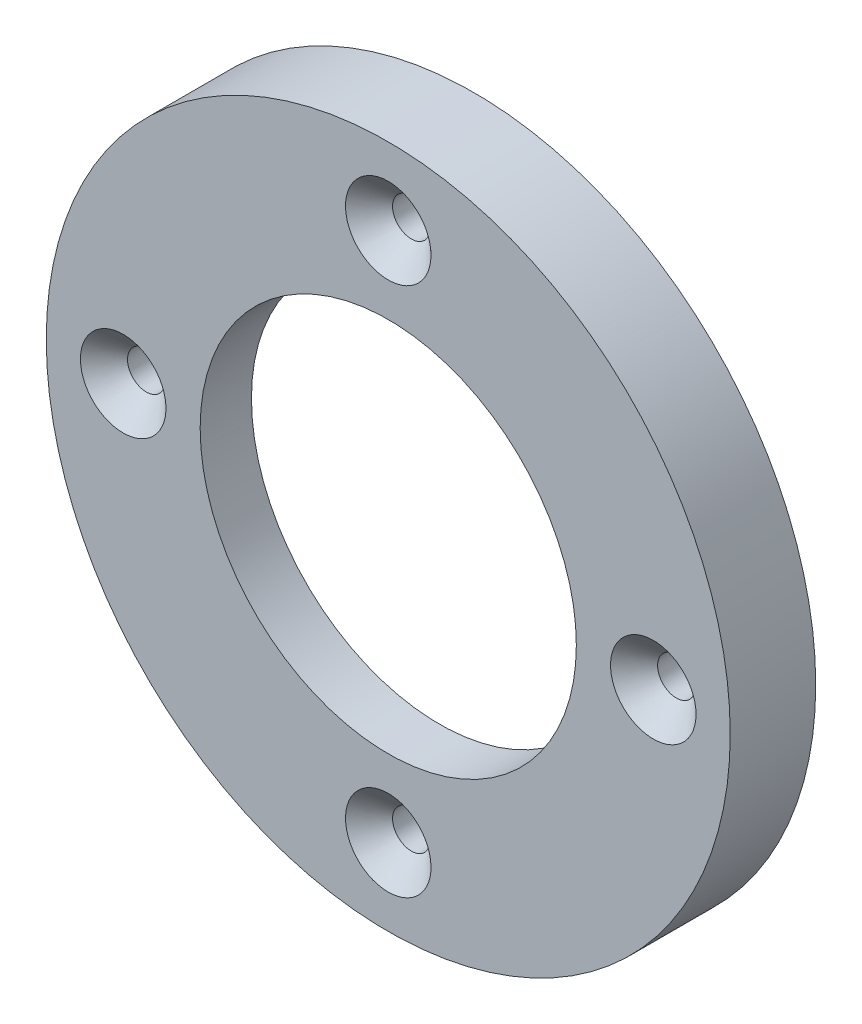
SolidWorks part; units mm, degrees
material "ABS"
ref_plane "Спереди" through (0, 0, 0) normal (0, 0, 1) x (1, 0, 0)
ref_plane "Сверху" through (0, 0, 0) normal (0, 1, 0) x (1, 0, 0)
ref_plane "Справа" through (0, 0, 0) normal (1, 0, 0) x (0, 0, -1)
sketch "Эскиз1" plane through (0, 0, 0) normal (0, 0, 1) x (1, 0, 0)
  arc A0 (-17.6855, -3.3502) -> (-3.3502, -17.6855) centre (0, 0) ccw
  circle A1 centre (0, 0) radius 15.5 construction
  arc A6 (-3.3502, 17.6855) -> (-17.6855, -3.3502) centre (0, 0) ccw
  arc A7 (17.6855, -3.3502) -> (-3.3502, 17.6855) centre (0, 0) ccw
  arc A8 (-3.3502, -17.6855) -> (17.6855, -3.3502) centre (0, 0) ccw
  point P18 (0, 0)
  dimension "D1" = 36
  dimension "D2" = 31
extrude "Бобышка-Вытянуть1" add sketch "Эскиз1" along normal blind 3
sketch "Эскиз2" plane through (0, 0, 3) normal (0, 0, 1) x (1, 0, 0)
  circle A0 centre (0, 0) radius 11
  dimension "D1" = 22
extrude "Вырез-Вытянуть1" cut sketch "Эскиз2" against normal through all
sketch "Эскиз3" plane through (0, 0, 3) normal (0, 0, 1) x (1, 0, 0)
  circle A0 centre (-15.5, 0) radius 2.2
  point P12 (0, 0)
  dimension "D1" = 4.4
  dimension "D2" = 15.5
sketch "Эскиз5" plane through (0, 0, 3) normal (0, 0, 1) x (1, 0, 0)
  circle A0 centre (0, 0) radius 18
  circle A1 centre (0, 0) radius 20
  dimension "D1" = 36
  dimension "D2" = 40
extrude "Бобышка-Вытянуть2" add sketch "Эскиз5" against normal blind 5
ref_axis "Ось1" through (-15.5, 0, -24.0809) along (0, 0, 1)
sketch "Эскиз6" plane through (0, 0, 0) normal (0, 1, 0) x (1, 0, 0)
  line L0 (-16.6, -1.648) -> (-18, -3)
  line L1 (-18, -3) -> (-15.5, -3)
  line L2 (-15.5, -1.648) -> (-15.5, -3)
  line L3 (-16.6, -1.648) -> (-16.6, 2)
  line L4 (-16.6, 2) -> (-15.5, 2)
  line L5 (-15.5, 2) -> (-15.5, -1.648)
  line L7 (-15.5, 24.0809) -> (-15.5, -65.7688) construction
  line L9 (20, 2) -> (-20, 2) construction
  line L10 (-17.7, -3) -> (-13.3, -3) construction
  point P6 (-15.5, -3)
  point P7 (0, 0)
  point P12 (0, 0)
  point P13 (0, 0)
  point P14 (-15.5, 2)
  dimension "D1" = 1.1
  dimension "D2" = 46
  dimension "D4" = 2.5
revolve "Вырез-Повернуть1" cut sketch "Эскиз6" angle 360 about axis through (-15.5, 0, -24.0809) along (0, 0, 1)
pattern_circular "Круговой массив1" count 4 over 360 about axis through (0, 0, 0) along (0, 0, 1) of "Вырез-Повернуть1"
chamfer "Фаска1" distance 0.5 angle 45 1 edges at (18, 0, -2)
